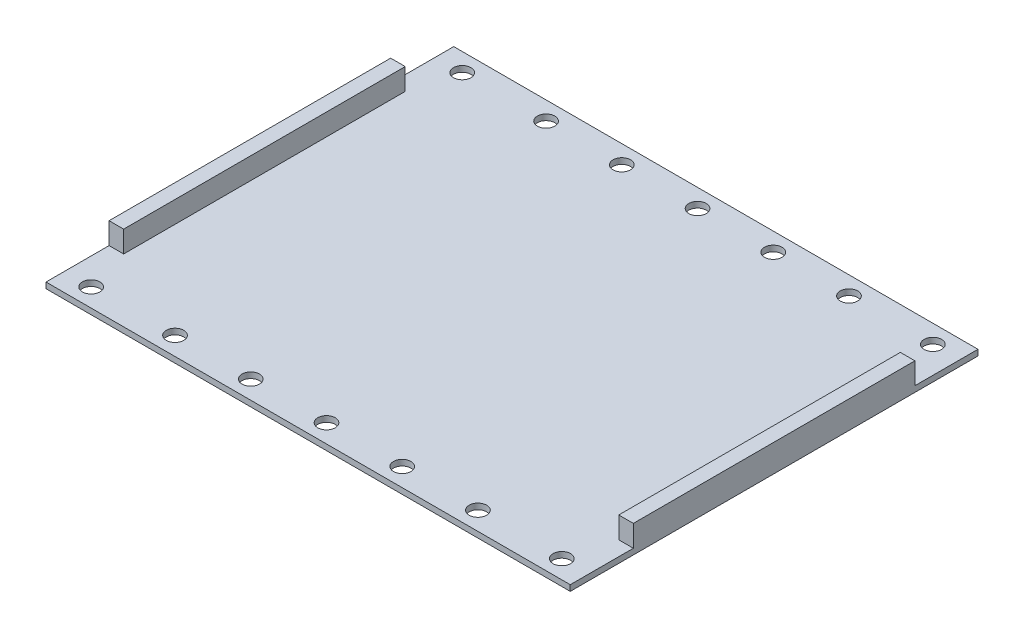
SolidWorks part; units mm, degrees
ref_plane "前视基准面" through (0, 0, 0) normal (0, 0, 1) x (1, 0, 0)
ref_plane "上视基准面" through (0, 0, 0) normal (0, 1, 0) x (1, 0, 0)
ref_plane "右视基准面" through (0, 0, 0) normal (1, 0, 0) x (0, 0, -1)
sketch "草图1" plane through (0, 0, 0) normal (0, 1, 0) x (1, 0, 0)
  line L0 (-45, 0) -> (45, 0) construction
  line L1 (-45, 35) -> (45, 35)
  line L2 (-45, 35) -> (-45, -35)
  line L3 (-45, -35) -> (45, -35)
  line L4 (45, 35) -> (45, -35)
  line L5 (-45, 35) -> (45, -35) construction
  line L6 (-45, -35) -> (45, 35) construction
  line L7 (0, -35) -> (0, 35) construction
  circle A0 centre (40.4, -31.85) radius 1.5
  circle A1 centre (-40.4, -31.85) radius 1.5
  circle A2 centre (40.4, 31.85) radius 1.5
  circle A3 centre (-40.4, 31.85) radius 1.5
  point P0 (0, 0)
  point P11 (0, 0)
  point P16 (0, 0)
  dimension "D3" = 1.65
  dimension "D4" = 3
  dimension "D5" = 3.1
  dimension "D1" = 70
  dimension "D2" = 90
extrude "凸台-拉伸1" add sketch "草图1" along normal blind 1
sketch "草图2" plane through (0, 1, 0) normal (0, 1, 0) x (1, 0, 0)
  line L0 (45, 0) -> (-45, 0) construction
  line L1 (45, -35) -> (45, 35) construction
  line L2 (-45, 35) -> (-45, -35) construction
  line L4 (42.5, -24.17) -> (45, -24.17)
  line L5 (42.5, -24.17) -> (42.5, 24.17)
  line L6 (42.5, 24.17) -> (45, 24.17)
  line L7 (45, -24.17) -> (45, 24.17)
  line L8 (42.5, -24.17) -> (45, 24.17) construction
  line L9 (42.5, 24.17) -> (45, -24.17) construction
  point P6 (43.75, 0)
  dimension "D1" = 2.5
  dimension "D2" = 48.34
extrude "凸台-拉伸2" add sketch "草图2" along normal blind 3.7
ref_plane "基准面1" through (0, 0, 0) normal (1, 0, 0) x (0, 0, -1)
mirror "镜向1" about plane through (0, 0, 0) normal (1, 0, 0) of "凸台-拉伸2"
sketch "草图4" plane through (0, 0, 0) normal (0, -1, 0) x (1, 0, 0)
  line L0 (-40.4, 31.85) -> (40.4, 31.85) construction
  line L4 (0, -3.3) -> (0, 3.3) construction
  circle A9 centre (0, 31.85) radius 1.5
  dimension "D1" = 3
extrude "切除-拉伸1" cut sketch "草图4" against normal blind 10
ref_plane "基准面2" through (0, 0, 0) normal (0, 0, 1) x (1, 0, 0)
pattern_linear "阵列(线性)1" count 3 spacing 13 along (-1, 0, 0) count 3 spacing 13 along (1, 0, 0) of "切除-拉伸1"
mirror "镜向2" about plane through (0, 0, 0) normal (0, 0, 1) of "阵列(线性)1", "切除-拉伸1"
